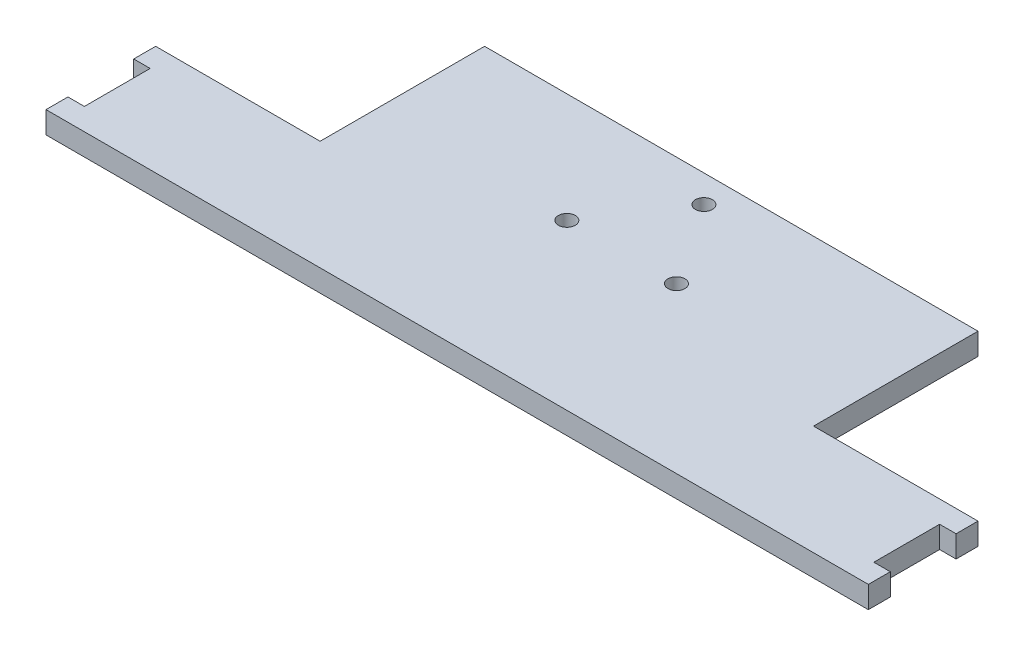
SolidWorks part; units mm, degrees
ref_plane "Alzado" through (0, 0, 0) normal (0, 0, 1) x (1, 0, 0)
ref_plane "Planta" through (0, 0, 0) normal (0, 1, 0) x (1, 0, 0)
ref_plane "Vista lateral" through (0, 0, 0) normal (1, 0, 0) x (0, 0, -1)
sketch "Croquis1" plane through (0, 0, 0) normal (0, 1, 0) x (1, 0, 0)
  line L0 (125, 40) -> (125, 0) construction
  line L1 (0, 0) -> (250, 0)
  line L2 (0, 0) -> (0, 250)
  line L3 (0, 250) -> (250, 250)
  line L4 (250, 0) -> (250, 250)
  line L5 (40, 40) -> (210, 40) construction
  line L6 (40, 40) -> (40, 210) construction
  line L7 (40, 210) -> (210, 210) construction
  line L8 (210, 40) -> (210, 210) construction
  line L9 (210, 125) -> (250, 125) construction
  circle A0 centre (40, 210) radius 2.5
  circle A1 centre (210, 210) radius 2.5
  circle A2 centre (210, 40) radius 2.5
  circle A3 centre (40, 40) radius 2.5
  dimension "D3" = 5
  dimension "D1" = 250
  dimension "D2" = 170
extrude "Saliente-Extruir1" add sketch "Croquis1" along normal blind 4
sketch "Croquis2" plane through (0, 4, 0) normal (0, 1, 0) x (1, 0, 0)
  line L0 (50, 125) -> (0, 125) construction
  line L1 (50, 50) -> (200, 50)
  line L2 (50, 50) -> (50, 150.0904)
  line L3 (50, 200) -> (200, 200)
  line L4 (200, 50) -> (200, 200)
  line L5 (0, 250) -> (0, 0) construction
  line L6 (125, 50) -> (125, 0) construction
  line L7 (0, 0) -> (250, 0) construction
  line L8 (50, 125) -> (200, 125) construction
  line L9 (125, 200) -> (125, 50) construction
  line L10 (48, 151.5) -> (48, 125) construction
  line L19 (50, 50) -> (200, 50) construction
  line L20 (50, 50) -> (50, 200) construction
  line L21 (50, 200) -> (200, 200) construction
  line L22 (200, 50) -> (200, 200) construction
  line L24 (50, 150.0904) -> (50, 172.9096)
  line L27 (59.9079, 125) -> (59.9079, 200) construction
  line L28 (50, 161.5) -> (34.9079, 161.5) construction
  line L29 (50, 150.0904) -> (125, 150.0904) construction
  line L30 (88.5, 200) -> (88.5, 125.0904) construction
  line L31 (78.5, 200) -> (98.5, 200)
  line L44 (121.5, 50) -> (101.5, 50)
  line L59 (88.5, 162.5452) -> (125, 162.5452) construction
  line L60 (42.454, 161.5) -> (42.454, 125) construction
  line L61 (25, 103.5) -> (25, 123.5) [skipped]
  line L65 (50, 150.0904) -> (50, 200)
  line L66 (125.0904, 175) -> (147.9096, 175) [skipped]
  line L69 (175, 146.5) -> (175, 126.5) [skipped]
  line L71 (150, 99.9096) -> (150, 77.0904) [skipped]
  line L72 (74.9096, 75) -> (52.0904, 75) [skipped]
  point P18 (50, 125)
  point P19 (125, 200)
  point P21 (0, 0)
  dimension "D1" = 150
  dimension "D2" = 150
  dimension "D4" = 4
  dimension "D6" = 36.5
extrude "Cortar-Extruir1" cut sketch "Croquis2" against normal blind 4
sketch "Croquis3" plane through (0, 4, 0) normal (0, 1, 0) x (1, 0, 0)
  line L0 (75, 175) -> (75, 75)
  line L1 (50, 200) -> (200, 200)
  line L2 (50, 200) -> (50, 50)
  line L3 (50, 50) -> (200, 50)
  line L4 (200, 200) -> (200, 50)
  line L5 (75, 75) -> (175, 75)
  line L6 (175, 175) -> (175, 75)
  line L7 (75, 175) -> (175, 175)
  dimension "D1" = 25
extrude "Saliente-Extruir2" add sketch "Croquis3" against normal up to surface (4 mm away) up to face at (125, 0, -125)
sketch "Croquis4" plane through (0, 4, 0) normal (0, 1, 0) x (1, 0, 0)
  line L0 (125, 0) -> (125, 75) construction
  line L1 (0, 0) -> (250, 0) construction
  line L2 (75, 75) -> (175, 75) construction
  line L3 (115, 20) -> (125, 20) construction
  line L4 (125, 20) -> (135, 20) construction
  circle A0 centre (115, 20) radius 1.55
  circle A1 centre (135, 20) radius 1.55
  circle A2 centre (125, 5) radius 1.55
  dimension "D1" = 3.1
  dimension "D4" = 5
  dimension "D2" = 10
  dimension "D3" = 20
extrude "Cortar-Extruir2" cut sketch "Croquis4" against normal blind 10
sketch "Croquis5" plane through (0, 4, 0) normal (0, 1, 0) x (1, 0, 0)
  line L0 (75, 175) -> (75, 75) construction
  line L1 (75, 75) -> (175, 75) construction
  line L2 (175, 75) -> (175, 175) construction
  line L3 (175, 175) -> (75, 175) construction
  line L4 (75, 175) -> (75, 75)
  line L5 (75, 75) -> (175, 75)
  line L6 (175, 75) -> (175, 175)
  line L7 (175, 175) -> (75, 175)
  line L8 (50, 200) -> (50, 50)
  line L9 (50, 50) -> (200, 50)
  line L10 (200, 50) -> (200, 200)
  line L11 (200, 200) -> (50, 200)
  dimension "D1" = 25
extrude "Cortar-Extruir3" cut sketch "Croquis5" against normal blind 10
sketch "Croquis6" plane through (0, 4, 0) normal (0, 1, 0) x (1, 0, 0)
  line L0 (250, 0) -> (250, 250) construction
  line L1 (250, 0) -> (170, 0)
  line L2 (250, 0) -> (250, 30)
  line L3 (250, 30) -> (170, 30)
  line L4 (170, 0) -> (170, 30)
  line L5 (220, 30) -> (250, 30)
  line L6 (220, 30) -> (220, 80)
  line L7 (220, 80) -> (250, 80)
  line L8 (250, 30) -> (250, 80)
  line L9 (50, 125) -> (200, 125) construction
  line L10 (50, 200) -> (50, 50) construction
  line L11 (200, 50) -> (200, 200) construction
  line L12 (125, 50) -> (125, 125) construction
  line L13 (50, 50) -> (200, 50) construction
  line L14 (0, 0) -> (30, 0)
  line L15 (0, 0) -> (0, 80)
  line L16 (0, 80) -> (30, 80)
  line L17 (30, 0) -> (30, 80)
  line L18 (30, 30) -> (80, 30)
  line L19 (30, 30) -> (30, 0)
  line L20 (30, 0) -> (80, 0)
  line L21 (80, 30) -> (80, 0)
  line L22 (0, 250) -> (0, 220)
  line L23 (0, 250) -> (80, 250)
  line L24 (80, 250) -> (80, 220)
  line L25 (0, 220) -> (80, 220)
  line L26 (30, 220) -> (30, 170)
  line L27 (30, 220) -> (0, 220)
  line L28 (0, 220) -> (0, 170)
  line L29 (30, 170) -> (0, 170)
  line L30 (250, 250) -> (220, 250)
  line L31 (250, 250) -> (250, 170)
  line L32 (250, 170) -> (220, 170)
  line L33 (220, 250) -> (220, 170)
  line L34 (220, 220) -> (170, 220)
  line L35 (220, 220) -> (220, 250)
  line L36 (220, 250) -> (170, 250)
  line L37 (170, 220) -> (170, 250)
  dimension "D1" = 30
  dimension "D2" = 80
  dimension "D3" = 80
  dimension "D4" = 4
extrude "Cortar-Extruir4" cut sketch "Croquis6" against normal blind 10 contours L2 L1 L4 L3 | L18 L21 L20 L19 | L14 L17 L16 L15 | L26 L29 L28 L27 | L22 L25 L24 L23 | L30 L33 L32 L31 | L34 L37 L36 L35 | L6 L5 L8 L7
sketch "Croquis8" plane through (0, 4, 0) normal (0, 1, 0) x (1, 0, 0)
  line L0 (50, 125) -> (200, 125) construction
  line L1 (50, 200) -> (50, 50) construction
  line L2 (200, 50) -> (200, 200) construction
  line L3 (125, 125) -> (125, 50) construction
  line L4 (50, 50) -> (200, 50) construction
  circle A0 centre (125, 5) radius 1.55 construction
  circle A1 centre (135, 20) radius 1.55 construction
  circle A2 centre (115, 20) radius 1.55 construction
  circle A3 centre (125, 5) radius 1.55
  circle A4 centre (135, 20) radius 1.55
  circle A5 centre (115, 20) radius 1.55
  circle A6 centre (20, 135) radius 1.55
  circle A7 centre (5, 125) radius 1.55
  circle A8 centre (20, 115) radius 1.55
  circle A9 centre (135, 230) radius 1.55
  circle A10 centre (125, 245) radius 1.55
  circle A11 centre (115, 230) radius 1.55
  circle A12 centre (230, 115) radius 1.55
  circle A13 centre (245, 125) radius 1.55
  circle A14 centre (230, 135) radius 1.55
  dimension "D1" = 4
extrude "Cortar-Extruir5" cut sketch "Croquis8" against normal blind 10
sketch "Croquis9" plane through (0, 4, 0) normal (0, 1, 0) x (1, 0, 0)
  line L2 (50, 0) -> (50, 34)
  line L8 (50, 200) -> (50, 50) construction
  line L9 (40, 40) -> (53, 40) construction
  line L10 (50, 46) -> (53, 46)
  line L12 (50, 34) -> (53, 34)
  line L13 (53, 46) -> (53, 34)
  line L14 (50, 46) -> (50, 204)
  line L15 (0, 125) -> (250, 125) construction
  line L16 (0, 170) -> (0, 80) construction
  line L17 (50, 216) -> (53, 216)
  line L18 (53, 204) -> (53, 216)
  line L19 (50, 204) -> (53, 204)
  line L20 (50, 216) -> (50, 250)
  line L21 (170, 250) -> (80, 250) construction
  line L22 (50, 250) -> (0, 250)
  line L23 (50, 250) -> (50, 216)
  line L24 (50, 0) -> (0, 0)
  line L25 (0, 250) -> (0, 0)
  line L26 (50, 204) -> (50, 46)
  line L27 (50, 34) -> (50, 0)
  line L28 (125, 0) -> (125, 50) construction
  line L29 (80, 0) -> (170, 0) construction
  line L30 (50, 50) -> (200, 50) construction
  line L31 (250, 250) -> (250, 0)
  line L32 (200, 250) -> (250, 250)
  line L33 (200, 204) -> (197, 204)
  line L34 (197, 204) -> (197, 216)
  line L35 (200, 216) -> (197, 216)
  line L36 (200, 216) -> (200, 250)
  line L37 (200, 0) -> (200, 34)
  line L38 (200, 46) -> (200, 204)
  line L39 (200, 46) -> (197, 46)
  line L40 (200, 34) -> (197, 34)
  line L41 (197, 46) -> (197, 34)
  line L42 (200, 0) -> (250, 0)
  circle M16 centre (5, 125) radius 1.55
  circle M17 centre (20, 115) radius 1.55
  circle M21 centre (20, 135) radius 1.55
  line M25 (50, 50) -> (50, 200)
  circle M32 centre (40, 210) radius 2.5
  circle M35 centre (40, 40) radius 2.5
  line M47 (80, 220) -> (30, 220)
  line M48 (30, 220) -> (30, 170)
  line M49 (30, 170) -> (0, 170)
  line M50 (0, 170) -> (0, 80)
  line M51 (0, 80) -> (30, 80)
  line M52 (30, 80) -> (30, 30)
  line M53 (30, 30) -> (80, 30)
  dimension "D1" = 12
  dimension "D2" = 3
extrude "Cortar-Extruir7" cut sketch "Croquis9" against normal blind 10 contours L17 L20 L2 L12 L13 L10 L14 L19 L18 M47 M48 M49 M50 M51 M52 M53 M25 M16 M32 M35 M21 M17 | L42 L31 L32 L36 L35 L34 L33 L38 L39 L41 L40 L37
sketch "Croquis10" plane through (0, 4, 0) normal (0, 1, 0) x (1, 0, 0)
  line L16 (200, 50) -> (50, 50)
  line L17 (50, 50) -> (50, 46)
  line L18 (50, 46) -> (53, 46)
  line L19 (53, 46) -> (53, 34)
  line L20 (53, 34) -> (50, 34)
  line L21 (50, 34) -> (50, 30)
  line L22 (50, 30) -> (80, 30)
  line L23 (80, 30) -> (80, 0)
  line L24 (80, 0) -> (170, 0)
  line L25 (170, 0) -> (170, 30)
  line L26 (170, 30) -> (200, 30)
  line L27 (200, 30) -> (200, 34)
  line L28 (200, 34) -> (197, 34)
  line L29 (197, 34) -> (197, 46)
  line L30 (197, 46) -> (200, 46)
  line L31 (200, 46) -> (200, 50)
  line L32 (200, 50) -> (50, 50)
  line L33 (50, 50) -> (50, 46)
  line L34 (50, 46) -> (53, 46)
  line L35 (53, 46) -> (53, 34)
  line L36 (53, 34) -> (50, 34)
  line L37 (50, 34) -> (50, 30)
  line L38 (50, 30) -> (80, 30)
  line L39 (80, 30) -> (80, 0)
  line L40 (80, 0) -> (170, 0)
  line L41 (170, 0) -> (170, 30)
  line L42 (170, 30) -> (200, 30)
  line L43 (200, 30) -> (200, 34)
  line L44 (200, 34) -> (197, 34)
  line L45 (197, 34) -> (197, 46)
  line L46 (197, 46) -> (200, 46)
  line L47 (200, 46) -> (200, 50)
  dimension "D1" = 0
extrude "Cortar-Extruir8" cut sketch "Croquis10" against normal blind 10
